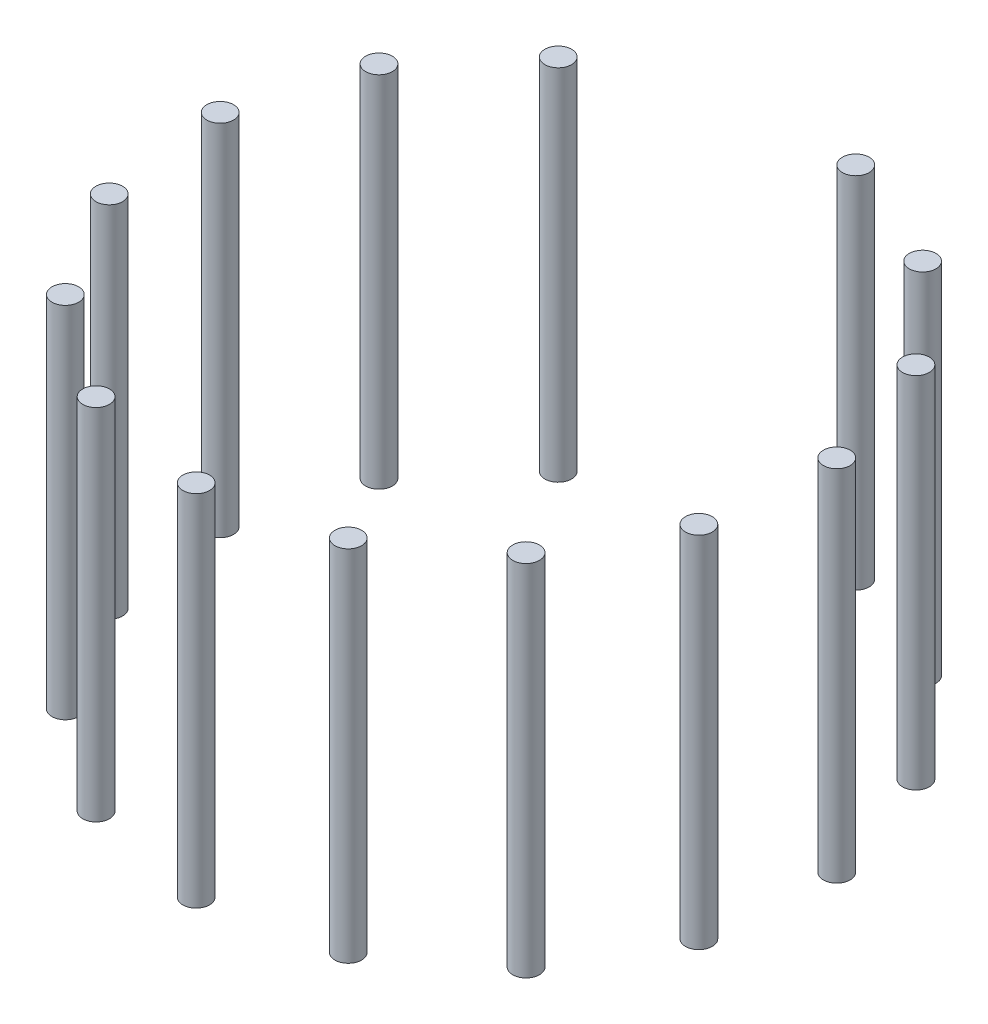
SolidWorks part; units mm, degrees
ref_plane "Front Plane" through (0, 0, 0) normal (0, 0, 1) x (1, 0, 0)
ref_plane "Top Plane" through (0, 0, 0) normal (0, 1, 0) x (1, 0, 0)
ref_plane "Right Plane" through (0, 0, 0) normal (1, 0, 0) x (0, 0, -1)
sketch "Sketch1" plane through (0, 0, 0) normal (0, 1, 0) x (1, 0, 0)
  line L0 (13.6308, 0.2761) -> (12.2956, 6.1256) construction
  line L1 (12.2956, 6.1256) -> (11.8506, 8.0755) construction
  circle A0 centre (15.1768, 8.1253) radius 0.35
  circle A1 centre (18.2357, 6.8178) radius 0.35
  circle A2 centre (20.4983, 4.3793) radius 0.35
  circle A3 centre (21.5735, 1.2312) radius 0.35
  circle A4 centre (21.2753, -2.082) radius 0.35
  circle A5 centre (19.6553, -4.9874) radius 0.35
  circle A6 centre (16.9936, -6.9828) radius 0.35
  circle A7 centre (13.7504, -7.723) radius 0.35
  circle A8 centre (10.4866, -7.0802) radius 0.35
  circle A9 centre (7.7663, -5.1653) radius 0.35
  circle A10 centre (6.0601, -2.3096) radius 0.35
  circle A11 centre (5.663, 0.9932) radius 0.35
  circle A12 centre (6.6435, 4.172) radius 0.35
  circle A13 centre (8.8322, 6.6771) radius 0.35
extrude "Boss-Extrude1" add sketch "Sketch1" along normal blind 9.4
